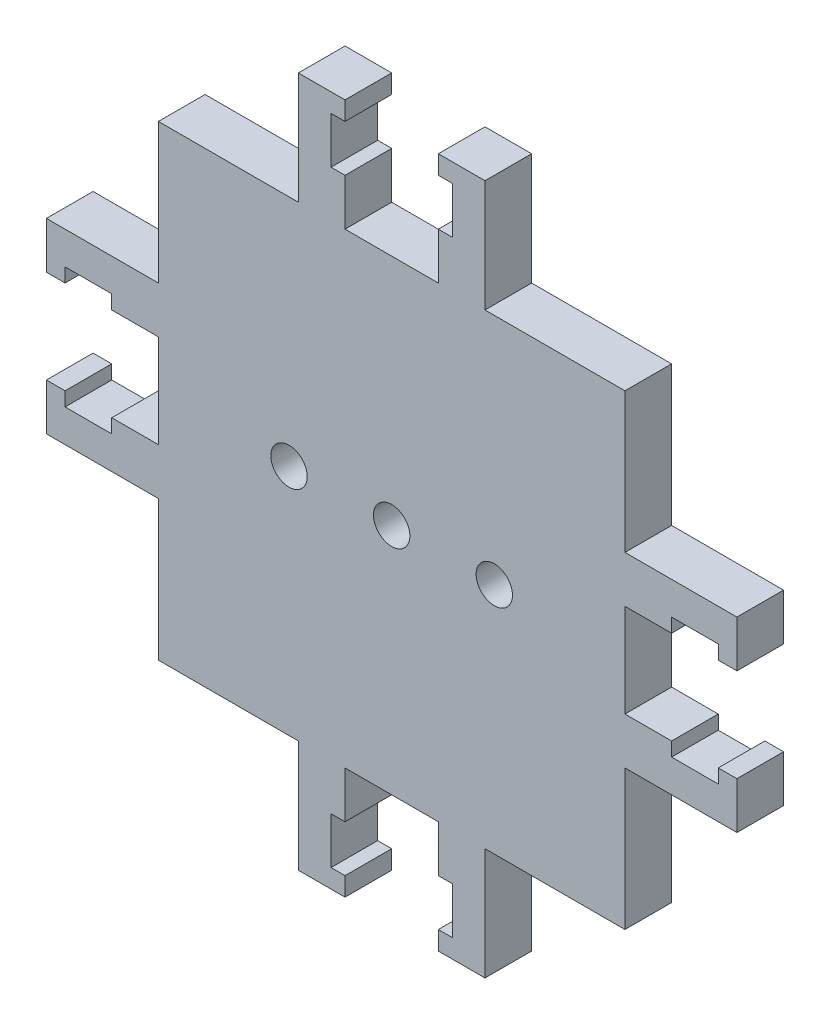
SolidWorks part; units mm, degrees
ref_plane "Plan de face" through (0, 0, 0) normal (0, 0, 1) x (1, 0, 0)
ref_plane "Plan de dessus" through (0, 0, 0) normal (0, 1, 0) x (1, 0, 0)
ref_plane "Plan de droite" through (0, 0, 0) normal (1, 0, 0) x (0, 0, -1)
sketch "Esquisse1" plane through (0, 0, 0) normal (0, 0, 1) x (1, 0, 0)
  line L0 (0, -10.9037) -> (0, 0) construction
  line L1 (0, 0) -> (78.1485, 0) construction
  line L2 (-25, 25) -> (-10, 25)
  line L3 (0, 0) -> (90.4553, 90.4553) construction
  line L4 (10, 25) -> (25, 25)
  line L5 (-25, -25) -> (-10, -25)
  line L6 (25, -25) -> (25, -10)
  line L8 (25, 10) -> (25, 25)
  line L9 (-25, -25) -> (-25, -10)
  line L10 (-25, 10) -> (-25, 25)
  line L13 (10, -25) -> (25, -25)
  circle A0 centre (0, 0) radius 1.95
  circle A1 centre (11, 0) radius 1.95
  circle A2 centre (-11, 0) radius 1.95
  line B0 (0, -25) -> (0, -13.135) construction
  line B1 (0, -25) -> (-5, -25)
  line B2 (-5, -30) -> (-10, -30) construction
  line B3 (-10, -30) -> (-10, -25)
  line B4 (-5, -30) -> (-5, -25)
  line B5 (0, -25) -> (5, -25)
  line B6 (5, -25) -> (5, -30)
  line B7 (5, -30) -> (10, -30) construction
  line B8 (10, -30) -> (10, -25)
  line B9 (-10, -30) -> (-10, -37)
  line B10 (-10, -37) -> (-5, -37)
  line B11 (-5, -37) -> (-5, -35)
  line B12 (-5, -35) -> (-6.5, -35)
  line B13 (-6.5, -35) -> (-6.5, -30)
  line B14 (-6.5, -30) -> (-5, -30)
  line B15 (5, -35) -> (6.5, -35)
  line B16 (10, -37) -> (5, -37)
  line B17 (5, -37) -> (5, -35)
  line B18 (6.5, -35) -> (6.5, -30)
  line B19 (10, -30) -> (10, -37)
  line B20 (10, -30) -> (10, -25)
  line B21 (5, -30) -> (6.5, -30)
  line B22 (0, -25) -> (0, -13.135) construction
  line B23 (0, -25) -> (5, -25)
  line B24 (5, -30) -> (10, -30) construction
  line B25 (10, -30) -> (10, -25)
  line B26 (5, -30) -> (5, -25)
  line B27 (0, -25) -> (-5, -25)
  line B28 (-5, -25) -> (-5, -30)
  line B29 (-5, -30) -> (-10, -30) construction
  line B30 (-10, -30) -> (-10, -25)
  line B31 (10, -30) -> (10, -37)
  line B32 (10, -37) -> (5, -37)
  line B33 (5, -37) -> (5, -35)
  line B34 (5, -35) -> (6.5, -35)
  line B35 (6.5, -35) -> (6.5, -30)
  line B36 (6.5, -30) -> (5, -30)
  line B37 (-5, -35) -> (-6.5, -35)
  line B38 (-10, -37) -> (-5, -37)
  line B39 (-5, -37) -> (-5, -35)
  line B40 (-6.5, -35) -> (-6.5, -30)
  line B41 (-10, -30) -> (-10, -37)
  line B42 (-10, -30) -> (-10, -25)
  line B43 (-5, -30) -> (-6.5, -30)
  line B44 (0, 25) -> (0, 13.135) construction
  line B45 (0, 25) -> (-5, 25)
  line B46 (-5, 30) -> (-10, 30) construction
  line B47 (-10, 30) -> (-10, 25)
  line B48 (-5, 30) -> (-5, 25)
  line B49 (0, 25) -> (5, 25)
  line B50 (5, 25) -> (5, 30)
  line B51 (5, 30) -> (10, 30) construction
  line B52 (10, 30) -> (10, 25)
  line B53 (-10, 30) -> (-10, 37)
  line B54 (-10, 37) -> (-5, 37)
  line B55 (-5, 37) -> (-5, 35)
  line B56 (-5, 35) -> (-6.5, 35)
  line B57 (-6.5, 35) -> (-6.5, 30)
  line B58 (-6.5, 30) -> (-5, 30)
  line B59 (5, 35) -> (6.5, 35)
  line B60 (10, 37) -> (5, 37)
  line B61 (5, 37) -> (5, 35)
  line B62 (6.5, 35) -> (6.5, 30)
  line B63 (10, 30) -> (10, 37)
  line B64 (10, 30) -> (10, 25)
  line B65 (5, 30) -> (6.5, 30)
  line B66 (25, 0) -> (13.135, 0) construction
  line B67 (25, 0) -> (25, -5)
  line B68 (30, -5) -> (30, -10) construction
  line B69 (30, -10) -> (25, -10)
  line B70 (30, -5) -> (25, -5)
  line B71 (25, 0) -> (25, 5)
  line B72 (25, 5) -> (30, 5)
  line B73 (30, 5) -> (30, 10) construction
  line B74 (30, 10) -> (25, 10)
  line B75 (30, -10) -> (37, -10)
  line B76 (37, -10) -> (37, -5)
  line B77 (37, -5) -> (35, -5)
  line B78 (35, -5) -> (35, -6.5)
  line B79 (35, -6.5) -> (30, -6.5)
  line B80 (30, -6.5) -> (30, -5)
  line B81 (35, 5) -> (35, 6.5)
  line B82 (37, 10) -> (37, 5)
  line B83 (37, 5) -> (35, 5)
  line B84 (35, 6.5) -> (30, 6.5)
  line B85 (30, 10) -> (37, 10)
  line B86 (30, 10) -> (25, 10)
  line B87 (30, 5) -> (30, 6.5)
  line B88 (-25, 0) -> (-13.135, 0) construction
  line B89 (-25, 0) -> (-25, -5)
  line B90 (-30, -5) -> (-30, -10) construction
  line B91 (-30, -10) -> (-25, -10)
  line B92 (-30, -5) -> (-25, -5)
  line B93 (-25, 0) -> (-25, 5)
  line B94 (-25, 5) -> (-30, 5)
  line B95 (-30, 5) -> (-30, 10) construction
  line B96 (-30, 10) -> (-25, 10)
  line B97 (-30, -10) -> (-37, -10)
  line B98 (-37, -10) -> (-37, -5)
  line B99 (-37, -5) -> (-35, -5)
  line B100 (-35, -5) -> (-35, -6.5)
  line B101 (-35, -6.5) -> (-30, -6.5)
  line B102 (-30, -6.5) -> (-30, -5)
  line B103 (-35, 5) -> (-35, 6.5)
  line B104 (-37, 10) -> (-37, 5)
  line B105 (-37, 5) -> (-35, 5)
  line B106 (-35, 6.5) -> (-30, 6.5)
  line B107 (-30, 10) -> (-37, 10)
  line B108 (-30, 10) -> (-25, 10)
  line B109 (-30, 5) -> (-30, 6.5)
  dimension "D11" = 3.9
  dimension "D4" = 3.9
  dimension "D2" = 50
  dimension "D3" = 50
  dimension "D5" = 45
  dimension "D6" = 11
sketch_block_instance "Insert plots ep 5mm avec ergots-1"
sketch_block "Insert plots ep 5mm avec ergots" parameters "D1"=10, "D2"=5, "D3"=5, "D4"=5, "D5"=2, "D6"=1.5, "D7"=2, "D8"=2, "D9"=2.0716, "D10"=2
sketch_block_instance "Insert plots ep 5mm avec ergots-3"
sketch_block_instance "Insert plots ep 5mm avec ergots-4"
sketch_block_instance "Insert plots ep 5mm avec ergots-6"
sketch_block_instance "Insert plots ep 5mm avec ergots-7"
extrude "Boss.-Extru.1" add sketch "Esquisse1" along normal blind 5
